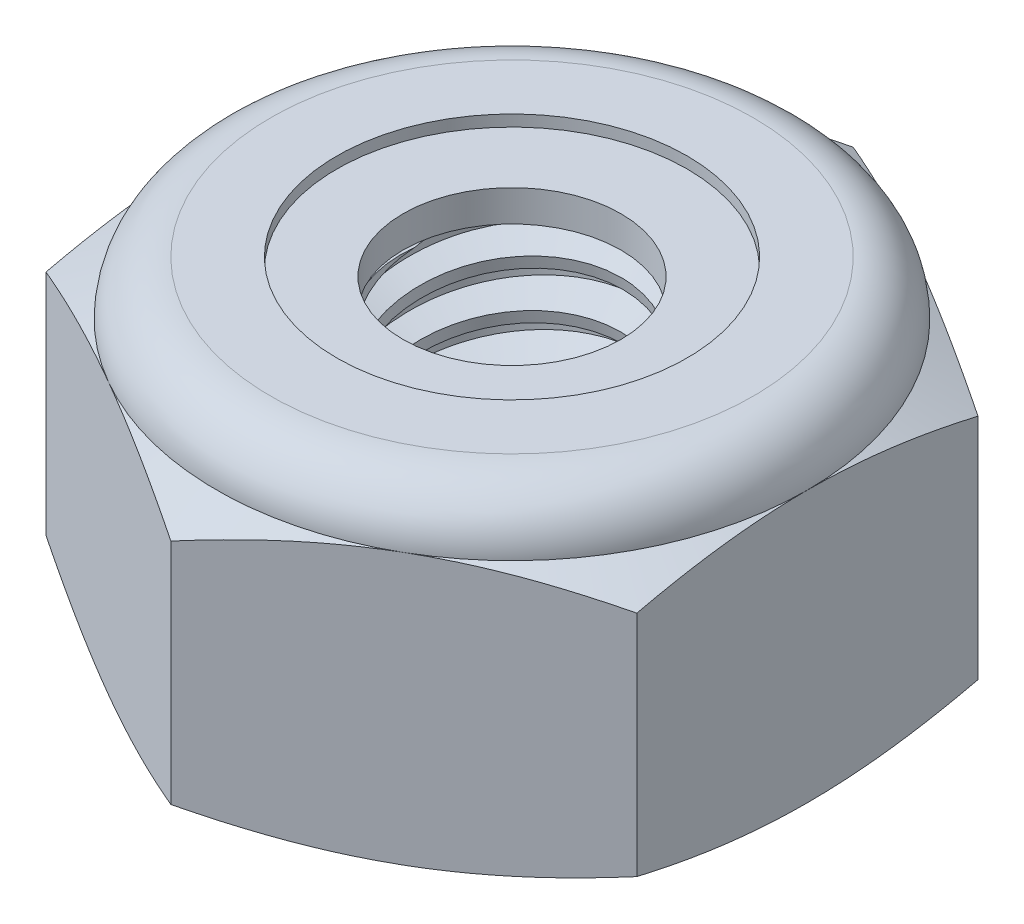
SolidWorks part; units mm, degrees
ref_plane "Front" through (0, 0, 0) normal (0, 0, 1) x (1, 0, 0)
ref_plane "Top" through (0, 0, 0) normal (0, 1, 0) x (1, 0, 0)
ref_plane "Right" through (0, 0, 0) normal (1, 0, 0) x (0, 0, -1)
sketch "Sketch1" plane through (0, 0, 0) normal (0, 1, 0) x (1, 0, 0)
  line L1 (0, 4.5827) -> (-3.9688, 2.2914)
  line L2 (-3.9688, 2.2914) -> (-3.9688, -2.2914)
  line L3 (-3.9688, -2.2914) -> (0, -4.5827)
  line L4 (0, -4.5827) -> (3.9688, -2.2914)
  line L5 (3.9688, -2.2914) -> (3.9687, 2.2914)
  line L6 (3.9687, 2.2914) -> (0, 4.5827)
  circle A0 centre (0, 0) radius 3.9688 construction
  dimension "Hex Flats" = 7.9375
extrude "Extrude1" add sketch "Sketch1" along normal blind 4.3656
sketch "Sketch2" plane through (0, 0, 0) normal (1, 0, 0) x (0, 0, -1)
  line L0 (-1.7526, 0) -> (-1.7526, 4.3656) construction
  line L1 (0, 0) -> (1.7526, 0)
  line L2 (0, 0) -> (0, 4.3656)
  line L3 (0, 4.3656) -> (1.7526, 4.3656)
  line L4 (1.7526, 0) -> (1.7526, 4.3656)
  line L5 (-2.2914, 4.3656) -> (2.2914, 4.3656) construction
  line L7 (0, -1.7526) -> (0, 0) construction
  dimension "Thread Dia" = 3.5052
revolve "Revolve1" add sketch "Sketch2" angle 360 about L7
sketch "Sketch3" plane through (0, 0, 0) normal (1, 0, 0) x (0, 0, -1)
  line L0 (1.7526, 4.3656) -> (-1.7526, 4.3656) construction
  line L1 (-1.7526, 4.3656) -> (-1.7526, 3.7306) construction
  line L2 (-1.7526, 3.7306) -> (1.7526, 4.3656) construction
  line L3 (1.7526, 4.3656) -> (1.7667, 4.2875) construction
  line L4 (1.7667, 4.2875) -> (1.8658, 3.7408)
  line L5 (1.8658, 3.7408) -> (1.4922, 3.8748)
  line L6 (1.4922, 3.8748) -> (1.4639, 4.031)
  line L7 (1.4639, 4.031) -> (1.7667, 4.2875)
  line L8 (1.4781, 3.9529) -> (1.8163, 4.0142) construction
  line L9 (1.7526, 4.3656) -> (1.7526, 4.0026) construction
  line L10 (1.7526, 4.0026) -> (-1.7526, 3.3676) construction
  line L11 (-1.7526, 3.3676) -> (-1.7526, 3.7306) construction
  line L12 (-0.1233, 4.3656) -> (0.1233, 3.0046) construction
  line L13 (-1.7526, 0) -> (-1.7526, 4.3656) construction
  line L14 (0, 4.3656) -> (1.7526, 4.3656) construction
  line L15 (1.7526, 0) -> (1.7526, 4.3656) construction
  point P13 (0, 3.6851)
  dimension "D1" = 0.0794
  dimension "D2" = 0.1588
  dimension "Thread Pitch" = 0.635
  dimension "D4" = 60
  dimension "D5" = 0.635
revolve "Cut-Revolve1" cut sketch "Sketch3" angle 360 about L12
pattern_linear "LPattern1" count 7 spacing 0.635 along (0, -1, 0) count 2 spacing 0.635 along (0, 1, 0) of "Cut-Revolve1"
sketch "Sketch4" plane through (0, 0, 0) normal (1, 0, 0) x (0, 0, -1)
  line L0 (0, 4.3656) -> (1.7526, 4.3656)
  line L1 (1.7526, 4.3656) -> (1.4639, 4.231)
  line L2 (1.4639, 4.231) -> (1.4639, 0.1346)
  line L3 (1.4639, 0.1346) -> (1.7526, 0)
  line L4 (1.7526, 0) -> (0, 0)
  line L5 (0, 0) -> (0, 4.3656)
  line L6 (1.7526, 0) -> (1.7526, 4.3656) construction
  line L7 (0, 4.3656) -> (1.7526, 4.3656) construction
  line L8 (0, 0) -> (1.7526, 0) construction
  line L9 (0, 0) -> (0, 4.3656) construction
  line L10 (0, 4.3656) -> (0, 4.6841) construction
  dimension "D1" = 25
revolve "Cut-Revolve2" cut sketch "Sketch4" angle 360 about L10
combine bodies "Combine1" operation type subtract main body 112 bodies to subtract 111
sketch "Sketch5" plane through (0, 0, 0) normal (1, 0, 0) x (0, 0, -1)
  line L0 (0, 0) -> (3.9688, 0)
  line L1 (3.9688, 0) -> (4.5827, 0.2863)
  line L2 (4.5827, 0.2863) -> (4.5827, 3.3517)
  line L3 (4.5827, 3.3517) -> (3.9688, 3.638)
  line L4 (3.2411, 4.3656) -> (3.2411, 5.6356)
  line L5 (3.2411, 5.6356) -> (5.8527, 5.6356)
  line L6 (5.8527, 5.6356) -> (5.8527, -1.27)
  line L7 (5.8527, -1.27) -> (0, -1.27)
  line L8 (0, -1.27) -> (0, 0)
  line L9 (3.9688, 3.638) -> (3.9688, 0) construction
  line L10 (0, 0) -> (1.7526, 0) construction
  line L13 (4.5827, 1.819) -> (5.8527, 1.819) construction
  line L14 (4.5827, 4.3656) -> (4.5827, 0) construction
  line L15 (0, 0) -> (0, 5.6356) construction
  line L20 (0, 5.6356) -> (3.2411, 5.6356) construction
  line L22 (0, 4.3656) -> (1.7526, 4.3656) construction
  arc A0 (3.9688, 3.638) -> (3.2411, 4.3656) centre (3.2411, 3.638) ccw
  dimension "D1" = 25
  dimension "D2" = 1.27
  dimension "D3" = 4.3656
  dimension "D4" = 0.7276
revolve "Cut-Revolve3" cut sketch "Sketch5" angle 360 about L15
sketch "Sketch6" plane through (0, 0, 0) normal (1, 0, 0) x (0, 0, -1)
  line L0 (0, 3.638) -> (3.8164, 3.638)
  line L1 (3.2411, 4.2132) -> (2.3525, 4.2132)
  line L2 (0, 5.6356) -> (0, 3.638)
  line L3 (2.3525, 5.6356) -> (0, 5.6356)
  line L4 (0, 5.6356) -> (3.2411, 5.6356) construction
  line L5 (0, 0) -> (0, 5.6356) construction
  line L6 (0, 5.6356) -> (0, 44.323) construction
  line L7 (2.3525, 4.2132) -> (2.3525, 5.6356)
  line L8 (3.2411, 4.3656) -> (3.2411, 4.2132) construction
  line L9 (2.3525, 4.2132) -> (1.4639, 4.2132) construction
  line L10 (1.4639, 4.2132) -> (1.4639, 4.231) construction
  arc A0 (3.8164, 3.638) -> (3.2411, 4.2132) centre (3.2411, 3.638) ccw
  arc A1 (3.9688, 3.638) -> (3.2411, 4.3656) centre (3.2411, 3.638) ccw construction
  dimension "D1" = 0.1524
revolve "Cut-Revolve4" cut sketch "Sketch6" angle 360 about L6
sketch "Sketch7" plane through (0, 0, 0) normal (1, 0, 0) x (0, 0, -1)
  line L0 (1.4639, 3.7142) -> (3.7343, 3.7142)
  line L1 (3.2411, 4.137) -> (1.4639, 4.137)
  line L2 (1.4639, 4.137) -> (1.4639, 3.7142)
  line L3 (1.4639, 3.7142) -> (0, 3.7142) construction
  line L4 (0, 3.7142) -> (0, 4.137) construction
  line L5 (0, 4.137) -> (1.4639, 4.137) construction
  line L6 (1.4639, 3.7142) -> (1.4639, 3.638) construction
  line L7 (0, 3.638) -> (3.8164, 3.638) construction
  line L8 (3.2411, 4.137) -> (3.2411, 4.2132) construction
  arc A0 (3.7343, 3.7142) -> (3.2411, 4.137) centre (3.2411, 3.638) ccw
  arc A2 (3.8164, 3.638) -> (3.2411, 4.2132) centre (3.2411, 3.638) ccw construction
  dimension "D1" = 0.0762
revolve "Revolve2" add sketch "Sketch7" angle 360 about L4
equation "\"D1@Sketch3\"=\"Thread Pitch@Sketch3\"/8"
equation "\"D2@Sketch3\"=\"Thread Pitch@Sketch3\"/4"
equation "\"D5@Sketch3\"=\"Thread Pitch@Sketch3\""
equation "\"D4@LPattern1\"=\"Thread Pitch@Sketch3\""
equation "\"D3@LPattern1\"=\"Thread Pitch@Sketch3\""
equation "\"D1@LPattern1\"=\"Height@Extrude1\"/\"Thread Pitch@Sketch3\""
equation "\"D4@Sketch5\"=\"Height@Extrude1\"/6"
